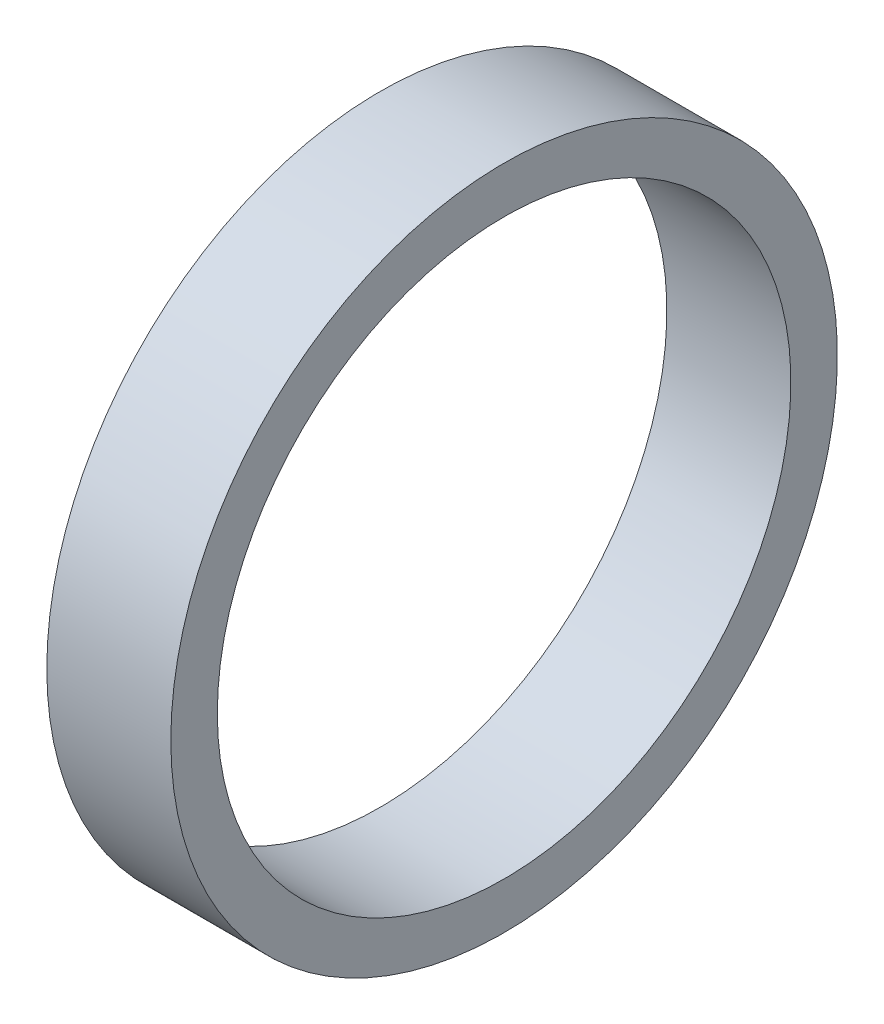
SolidWorks part; units mm, degrees
ref_plane "Front Plane" through (0, 0, 0) normal (0, 0, 1) x (1, 0, 0)
ref_plane "Top Plane" through (0, 0, 0) normal (0, 1, 0) x (1, 0, 0)
ref_plane "Right Plane" through (0, 0, 0) normal (1, 0, 0) x (0, 0, -1)
sketch "Axial profile (mm)" plane through (0, 0, 0) normal (0, 0, 1) x (1, 0, 0)
  line L0 (-110, 0) -> (75, 0) construction
  line L1 (-2.4, 11.1) -> (2.4, 11.1)
  line L2 (2.4, 11.1) -> (2.4, 12.9)
  line L3 (2.4, 12.9) -> (-2.4, 12.9)
  line L4 (-2.4, 12.9) -> (-2.4, 11.1)
revolve "Full revolution" add sketch "Axial profile (mm)" angle 360 about L0
